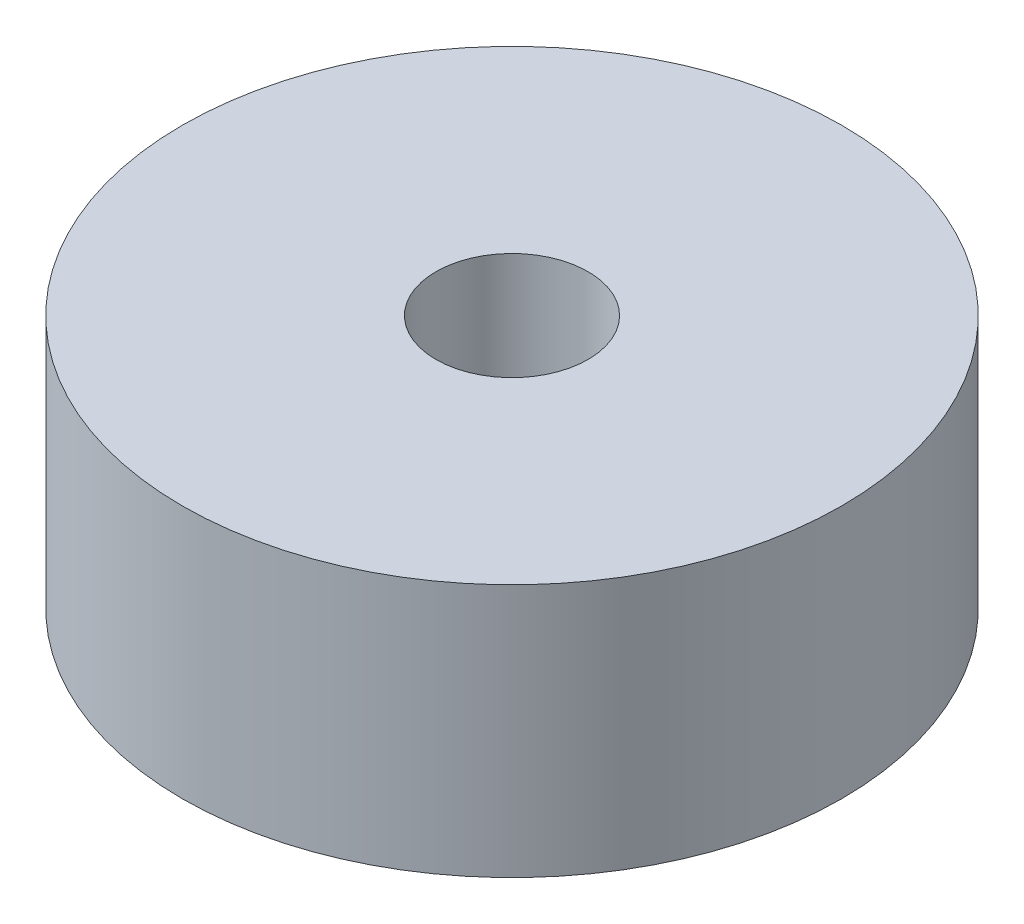
SolidWorks part; units mm, degrees
material "Пластичное железо"
ref_plane "Спереди" through (0, 0, 0) normal (0, 0, 1) x (1, 0, 0)
ref_plane "Сверху" through (0, 0, 0) normal (0, 1, 0) x (1, 0, 0)
ref_plane "Справа" through (0, 0, 0) normal (1, 0, 0) x (0, 0, -1)
sketch "Эскиз1" plane through (0, 0, 0) normal (0, 1, 0) x (1, 0, 0)
  circle A0 centre (0, 0) radius 6.5
  circle A1 centre (0, 0) radius 1.5
extrude "Бобышка-Вытянуть2" add sketch "Эскиз1" against normal blind 5
